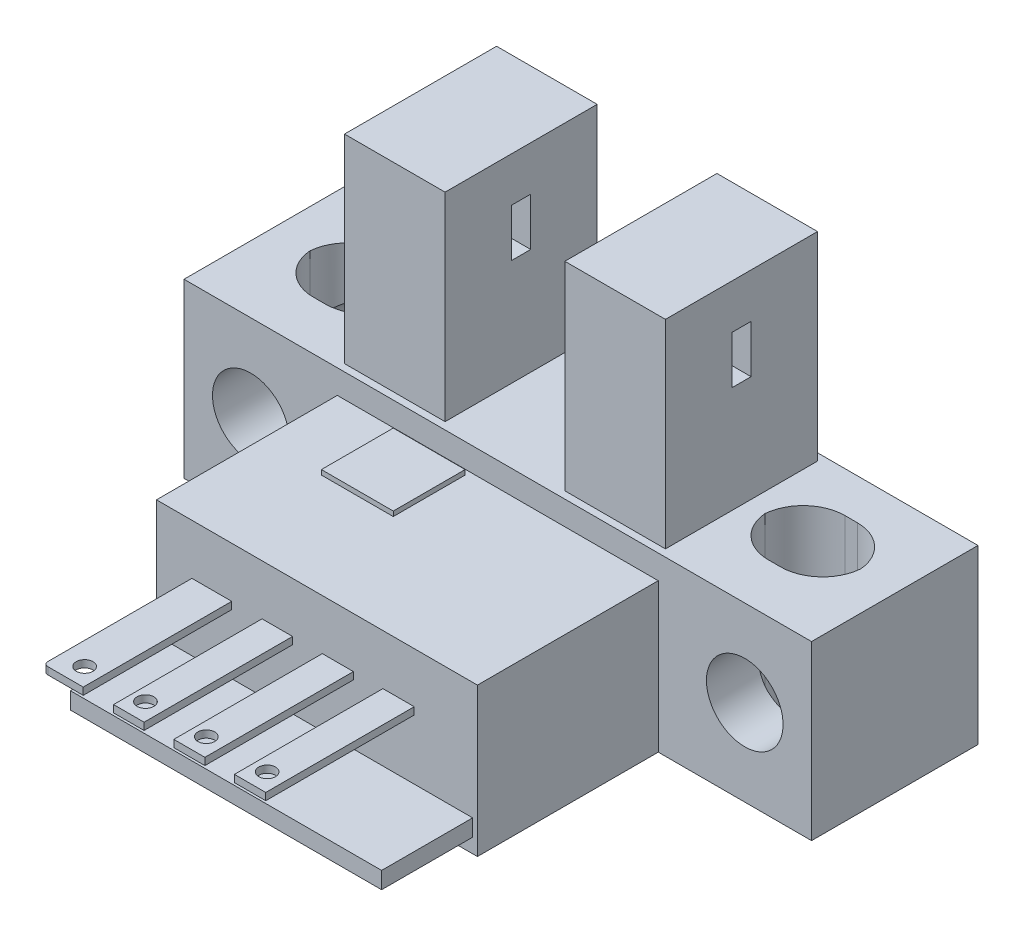
SolidWorks part; units mm, degrees
ref_plane "Front Plane" through (0, 0, 0) normal (0, 0, 1) x (1, 0, 0)
ref_plane "Top Plane" through (0, 0, 0) normal (0, 1, 0) x (1, 0, 0)
ref_plane "Right Plane" through (0, 0, 0) normal (1, 0, 0) x (0, 0, -1)
sketch "Sketch1" plane through (0, 0, 0) normal (0, 0, 1) x (1, 0, 0)
  line L0 (-13.1, 3.6) -> (13.1, 3.6) construction
  line L1 (0, 40.9179) -> (0, -26.127) construction
  line L2 (-13.1, 0) -> (13.1, 0)
  line L3 (-13.1, 0) -> (-13.1, 7.2)
  line L4 (-13.1, 7.2) -> (13.1, 7.2)
  line L5 (13.1, 0) -> (13.1, 7.2)
  circle A0 centre (-10.3118, 3.6) radius 1.6
  circle A1 centre (10.3118, 3.6) radius 1.6
  dimension "D3" = 3.2
  dimension "D1" = 7.2
  dimension "D2" = 26.2
extrude "Boss-Extrude1" add sketch "Sketch1" along normal blind 6.95
ref_plane "Plane4" through (0, 0, 3.475) normal (0, 0, 1) x (1, 0, 0)
sketch "Sketch2" plane through (0, 0, 3.475) normal (0, 0, 1) x (1, 0, 0)
  line L0 (0, -3.8403) -> (0, 16.1665) construction
  line L1 (13.1, 7.2) -> (-13.1, 7.2) construction
  line L2 (-6.7, 7.2) -> (6.7, 7.2)
  line L3 (-6.7, 7.2) -> (-6.7, 15.5)
  line L4 (-6.7, 15.5) -> (-2.5, 15.5)
  line L5 (6.7, 7.2) -> (6.7, 15.5)
  line L6 (2.5, 15.5) -> (6.7, 15.5)
  line L8 (-2.5, 15.5) -> (-2.5, 7.2)
  line L9 (-2.5, 7.2) -> (2.5, 7.2)
  line L10 (2.5, 15.5) -> (2.5, 7.2)
  line L11 (-13.1, 0) -> (13.1, 0) construction
  dimension "D1" = 5
  dimension "D2" = 13.4
  dimension "D3" = 15.5
extrude "Boss-Extrude2" add sketch "Sketch2" along normal blind 3.175 and the other way blind 3.175 contours L8 L4 L3 L2 | L6 L10 L2 L5
sketch "Sketch3" plane through (-6.7, 0, 0) normal (-1, 0, 0) x (0, 0, 1)
  line L0 (3.475, 7.2) -> (3.475, 15.5) construction
  line L1 (0.3, 7.2) -> (6.65, 7.2) construction
  line L2 (0.3, 15.5) -> (6.65, 15.5) construction
  line L4 (3.075, 11.64) -> (3.875, 11.64)
  line L5 (3.075, 11.64) -> (3.075, 13.64)
  line L6 (3.075, 13.64) -> (3.875, 13.64)
  line L7 (3.875, 11.64) -> (3.875, 13.64)
  line L8 (3.075, 11.64) -> (3.875, 13.64) construction
  line L9 (3.075, 13.64) -> (3.875, 11.64) construction
  point P6 (3.475, 12.64)
  dimension "D1" = 2
  dimension "D2" = 0.8
  dimension "D3" = 5.44
extrude "Cut-Extrude1" cut sketch "Sketch3" against normal through all
sketch "Sketch4" plane through (0, 0, 6.95) normal (0, 0, 1) x (1, 0, 0)
  line L0 (0, -2.3229) -> (0, 19.9434) construction
  line L1 (-13.1, 0) -> (13.1, 0) construction
  line L2 (-6.7, 0) -> (6.7, 0)
  line L3 (-6.7, 0) -> (-6.7, 6.2)
  line L4 (-6.7, 6.2) -> (6.7, 6.2)
  line L5 (6.7, 0) -> (6.7, 6.2)
  dimension "D1" = 6.2
  dimension "D2" = 13.4
extrude "Boss-Extrude3" add sketch "Sketch4" along normal blind 7.55
sketch "Sketch5" plane through (0, 0, 14.5) normal (0, 0, 1) x (1, 0, 0)
  line L0 (0, -1.1433) -> (0, 5.7073) construction
  line L1 (-6.7, 0) -> (6.7, 0) construction
  line L3 (6.5, 1.3) -> (-6.5, 1.3)
  line L4 (6.5, 1.3) -> (6.5, 0.6)
  line L5 (6.5, 0.6) -> (-6.5, 0.6)
  line L6 (-6.5, 1.3) -> (-6.5, 0.6)
  dimension "D1" = 0.6
  dimension "D2" = 0.7
  dimension "D3" = 13
extrude "Boss-Extrude4" add sketch "Sketch5" along normal blind 3.8
sketch "Sketch6" plane through (0, 0, 14.5) normal (0, 0, 1) x (1, 0, 0)
  line L0 (0, 5.8289) -> (0, -1.0054) construction
  line L1 (6.7, 6.2) -> (-6.7, 6.2) construction
  line L2 (-5.5288, 4.1) -> (5.5288, 4.1)
  line L3 (-5.5288, 4.1) -> (-5.5288, 3.8)
  line L4 (-5.5288, 3.8) -> (5.5288, 3.8)
  line L5 (5.5288, 4.1) -> (5.5288, 3.8)
  dimension "D1" = 0.3
  dimension "D2" = 2.1
extrude "Boss-Extrude5" add sketch "Sketch6" along normal blind 6.2
sketch "Sketch7" plane through (0, 4.1, 0) normal (0, 1, 0) x (1, 0, 0)
  line L0 (5.5288, -20.7) -> (-5.5288, -20.7) construction
  line L1 (-3.5581, -20.7) -> (-2.8844, -20.7)
  line L2 (-3.5581, -20.7) -> (-3.5581, -14.5)
  line L3 (-3.5581, -14.5) -> (-2.8844, -14.5)
  line L4 (-2.8844, -20.7) -> (-2.8844, -14.5)
  line L5 (6.7, -14.5) -> (-6.7, -14.5) construction
  line L6 (-1.0181, -20.7) -> (-1.0181, -14.5)
  line L7 (-1.0181, -20.7) -> (-0.3444, -20.7)
  line L8 (-0.3444, -20.7) -> (-0.3444, -14.5)
  line L9 (-1.0181, -14.5) -> (-0.3444, -14.5)
  line L10 (1.5219, -20.7) -> (1.5219, -14.5)
  line L11 (1.5219, -20.7) -> (2.1956, -20.7)
  line L12 (2.1956, -20.7) -> (2.1956, -14.5)
  line L13 (1.5219, -14.5) -> (2.1956, -14.5)
  line L14 (4.0619, -20.7) -> (4.0619, -14.5)
  line L15 (4.0619, -20.7) -> (4.7356, -20.7)
  line L16 (4.7356, -20.7) -> (4.7356, -14.5)
  line L17 (4.0619, -14.5) -> (4.7356, -14.5)
  line L18 (6.5, -14.5) -> (-6.5, -14.5) construction
  line L19 (-5.22, -20.7) -> (-5.5288, -20.7)
  line L20 (-5.22, -20.7) -> (-5.22, -14.5)
  line L21 (-5.22, -14.5) -> (-5.5288, -14.5)
  line L22 (-5.5288, -20.7) -> (-5.5288, -14.5)
  line L23 (-5.5288, -20.7) -> (5.5288, -20.7)
  line L24 (5.5288, -20.7) -> (5.5288, -14.5)
  line L25 (5.5288, -14.5) -> (-5.5288, -14.5)
  line L27 (-2.292, -20.7) -> (-2.8844, -20.7)
  line L28 (-2.292, -20.7) -> (-2.292, -14.5)
  line L29 (-2.292, -14.5) -> (-2.8844, -14.5)
  line L30 (-2.8844, -20.7) -> (-2.8844, -14.5)
  line L31 (-0.3444, -20.7) -> (0.2239, -20.7)
  line L32 (-0.3444, -20.7) -> (-0.3444, -14.5)
  line L33 (-0.3444, -14.5) -> (0.2239, -14.5)
  line L34 (0.2239, -20.7) -> (0.2239, -14.5)
  line L35 (2.1956, -20.7) -> (2.7541, -20.7)
  line L36 (2.1956, -20.7) -> (2.1956, -14.5)
  line L37 (2.1956, -14.5) -> (2.7541, -14.5)
  line L38 (2.7541, -20.7) -> (2.7541, -14.5)
  circle A0 centre (-4.2739, -19.9263) radius 0.35
  circle A1 centre (-1.7339, -19.9263) radius 0.35
  circle A2 centre (0.8061, -19.9263) radius 0.35
  circle A3 centre (3.3461, -19.9263) radius 0.35
  arc A5 (-5.22, -20.5178) -> (-5.0378, -20.7) centre (-5.0378, -20.5178) ccw
  line M26 (5.5288, -14.5) -> (-5.5288, -14.5)
  line M27 (-5.5288, -14.5) -> (-5.5288, -20.7)
  line M28 (-5.5288, -20.7) -> (5.5288, -20.7)
  line M29 (5.5288, -20.7) -> (5.5288, -14.5)
  dimension "D1" = 0.7
  dimension "D2" = 4
  dimension "D3" = 4
extrude "Cut-Extrude3" cut sketch "Sketch7" against normal blind 2 contours L20 M28 M26 M27 | A0 | L4 L2 M28 M26 | L28 L25 L4 M28 | A1 | L8 L6 M28 M26 | L34 L25 L8 M28 | L12 L10 M28 M26 | L38 L25 L12 M28 | L16 L14 M28 M26 | L16 M28 M29 M26 | A5 L20 M28 | A2 | A3
sketch "Sketch9" plane through (0, 7.2, 0) normal (0, 1, 0) x (1, 0, 0)
  line L0 (0, 0) -> (0, -18.3) construction
  line L1 (6.5, -18.3) -> (-6.5, -18.3) construction
  line L2 (-9.5, -3.297) -> (-9.5, -5.2863) construction
  line L3 (9.2436, -4.897) -> (9.7564, -4.897)
  line L4 (13.1, -6.95) -> (13.1, 0) construction
  line L5 (-9.2436, -4.897) -> (-9.7564, -4.897)
  line L11 (-9.2436, -1.697) -> (-9.7564, -1.697)
  line L13 (0, -3.475) -> (13.1, -3.475) construction
  line L14 (-7.1999, -4.897) -> (-11.8001, -1.697) construction
  line L15 (-7.1999, -1.697) -> (-11.8001, -4.897) construction
  line L16 (-6.9153, -3.297) -> (-12.0098, -3.297) construction
  line L17 (9.2436, -1.697) -> (9.7564, -1.697)
  arc A3 (-9.7564, -1.697) -> (-11.5, -3.297) centre (-9.7564, -3.447) ccw
  arc A4 (-9.7564, -4.897) -> (-11.5, -3.297) centre (-9.7564, -3.147) cw
  arc A5 (-9.2436, -4.897) -> (-7.5, -3.297) centre (-9.2436, -3.147) ccw
  arc A6 (-9.2436, -1.697) -> (-7.5, -3.297) centre (-9.2436, -3.447) cw
  arc A7 (9.2436, -1.697) -> (7.5, -3.297) centre (9.2436, -3.447) ccw
  arc A8 (9.2436, -4.897) -> (7.5, -3.297) centre (9.2436, -3.147) cw
  arc A9 (9.7564, -4.897) -> (11.5, -3.297) centre (9.7564, -3.147) ccw
  arc A10 (9.7564, -1.697) -> (11.5, -3.297) centre (9.7564, -3.447) cw
  point P7 (-9.5, -3.297)
  point P11 (-9.5, -3.297)
  dimension "D1" = 3.2
  dimension "D2" = 3.5
  dimension "D3" = 9.5
  dimension "D4" = 4
extrude "Cut-Extrude4" cut sketch "Sketch9" against normal through all
sketch "Sketch10" plane through (0, 6.2, 0) normal (0, 1, 0) x (1, 0, 0)
  line L1 (-4.1505, -10.163) -> (-1.1505, -10.163)
  line L2 (-4.1505, -10.163) -> (-4.1505, -7.163)
  line L3 (-4.1505, -7.163) -> (-1.1505, -7.163)
  line L4 (-1.1505, -10.163) -> (-1.1505, -7.163)
  line L5 (-4.1505, -10.163) -> (-1.1505, -7.163) construction
  line L6 (-4.1505, -7.163) -> (-1.1505, -10.163) construction
  point P0 (-2.6505, -8.663)
  dimension "D1" = 3
  dimension "D2" = 3
extrude "Boss-Extrude6" add sketch "Sketch10" along normal blind 0.2
